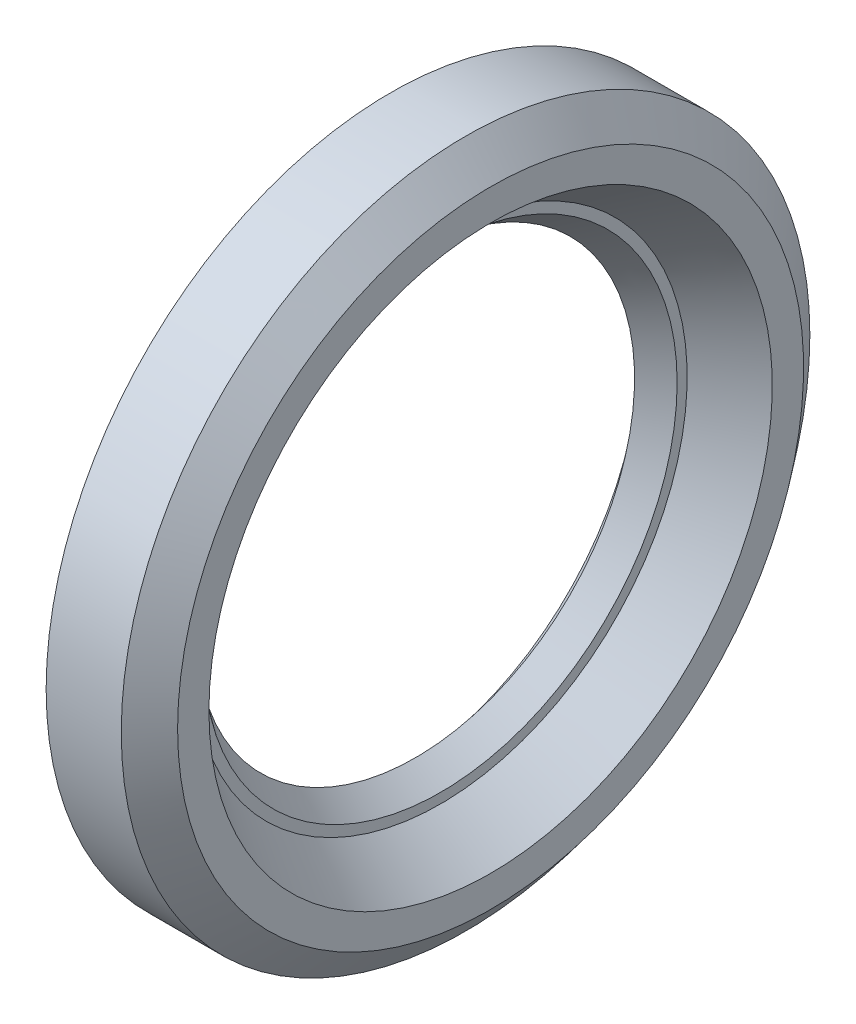
SolidWorks part; units mm, degrees
material "Силиконовая резина"
ref_plane "Спереди" through (0, 0, 0) normal (0, 0, 1) x (1, 0, 0)
ref_plane "Сверху" through (0, 0, 0) normal (0, 1, 0) x (1, 0, 0)
ref_plane "Справа" through (0, 0, 0) normal (1, 0, 0) x (0, 0, -1)
sketch "Эскиз1" plane through (0, 0, 0) normal (0, 0, 1) x (1, 0, 0)
  line L0 (-1000, 0) -> (49000, 0) construction
  line L16 (0, 17.5) -> (8, 17.5) construction
  line L17 (0, 17.5) -> (0, 27.5) construction
  line L18 (0, 27.5) -> (8, 27.5) construction
  line L19 (8, 17.5) -> (8, 27.5) construction
  dimension "_h_" = 8
  dimension "_D" = 55
  dimension "_d_" = 35
sketch "Эскиз2" plane through (0, 0, 0) normal (0, 0, 1) x (1, 0, 0)
  line L1 (0, 27.5) -> (0, 25) construction
  line L3 (0, 25) -> (0, 22.5) construction
  line L8 (0, 22.5) -> (0, 20) construction
  line L13 (0, 20) -> (0, 17.5) construction
  line L15 (0, 25) -> (8, 25) construction
  line L16 (0, 17.5) -> (0, 27.5) construction
  line L17 (8, 17.5) -> (8, 27.5) construction
  line L20 (4, 27.5) -> (4, 17.5) construction
  line L21 (0, 27.5) -> (8, 27.5) construction
  line L22 (0, 17.5) -> (8, 17.5) construction
  line L23 (0, 27.5) -> (4, 27.5) construction
  line L25 (2, 27.5) -> (2, 17.5) construction
  line L27 (2, 17.5) -> (1.5, 18.125) construction
  line L28 (1.5, 18.125) -> (1, 18.75) construction
  line L29 (1, 18.75) -> (0.5, 19.375) construction
  line L30 (0.5, 19.375) -> (0, 20) construction
  line L32 (0.5, 19.375) -> (0.5, 27.5) construction
  line L33 (4, 27.5) -> (8, 27.5) construction
  line L34 (6, 27.5) -> (6, 17.5) construction
  line L35 (8, 25) -> (6, 27.5)
  line L36 (6, 27.5) -> (0, 27.5)
  line L37 (0, 27.5) -> (0, 25)
  line L38 (0, 25) -> (4, 25)
  line L39 (4, 25) -> (4, 22.5)
  line L40 (4, 22.5) -> (0.5, 22.5)
  line L41 (0.5, 22.5) -> (0.5, 19.375)
  line L42 (0.5, 19.375) -> (2, 17.5)
  line L43 (2, 17.5) -> (4, 18.8999)
  line L44 (4, 18.8999) -> (4, 19.7003)
  line L45 (4, 19.7003) -> (8, 22.5)
  line L46 (8, 22.5) -> (8, 25)
revolve "Повернуть2" add sketch "Эскиз2" angle 360 about L0
